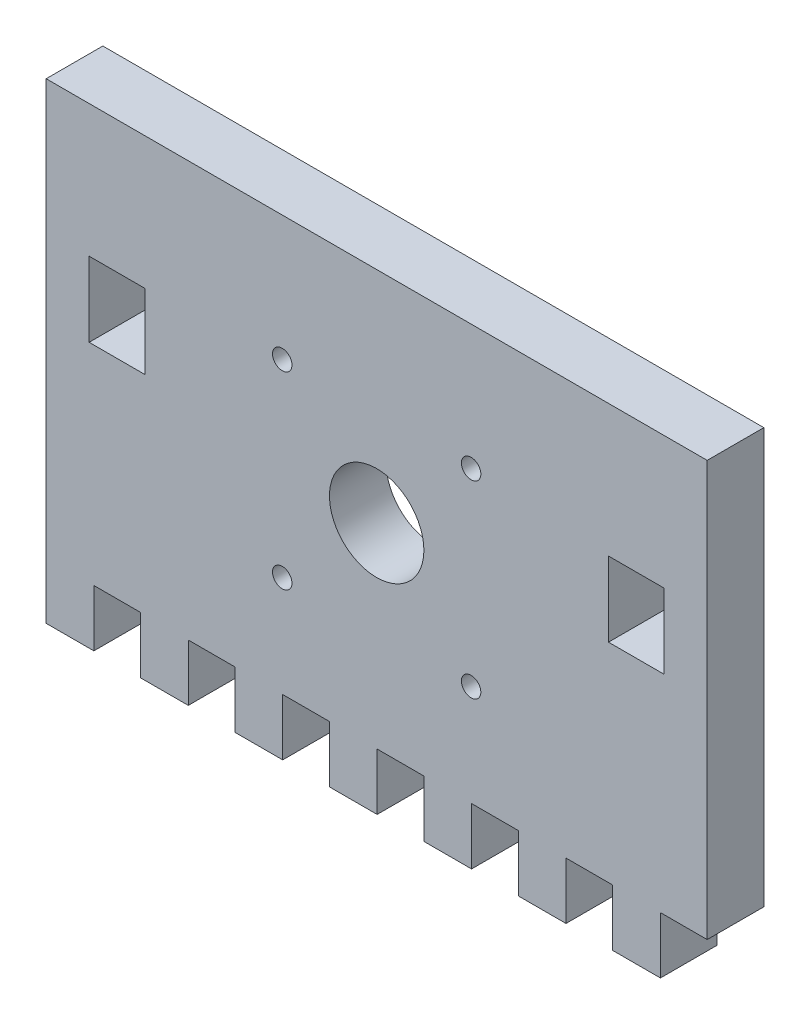
SolidWorks part; units mm, degrees
ref_plane "Plan de face" through (0, 0, 0) normal (0, 0, 1) x (1, 0, 0)
ref_plane "Plan de dessus" through (0, 0, 0) normal (0, 1, 0) x (1, 0, 0)
ref_plane "Plan de droite" through (0, 0, 0) normal (1, 0, 0) x (0, 0, -1)
sketch "Esquisse1" plane through (0, 0, 0) normal (0, 0, 1) x (1, 0, 0)
  line L0 (0, 0) -> (0, 49.95)
  line L1 (0, 49.95) -> (70, 49.95)
  line L2 (70, 49.95) -> (70, 6)
  line L3 (70, 6) -> (65.05, 6)
  line L4 (65.05, 6) -> (65.05, 0)
  line L5 (65.05, 0) -> (60, 0)
  line L6 (60, 0) -> (60, 6)
  line L7 (60, 6) -> (55.05, 6)
  line L8 (55.05, 6) -> (55.05, 0)
  line L10 (30, 0) -> (30, 6)
  line L11 (30, 6) -> (25.05, 6)
  line L12 (25.05, 6) -> (25.05, 0)
  line L13 (25.05, 0) -> (20, 0)
  line L14 (20, 0) -> (20, 6)
  line L15 (20, 6) -> (15.05, 6)
  line L16 (15.05, 6) -> (15.05, 0)
  line L17 (15.05, 0) -> (10, 0)
  line L18 (10, 0) -> (10, 6)
  line L19 (10, 6) -> (5.05, 6)
  line L20 (5.05, 6) -> (5.05, 0)
  line L21 (5.05, 0) -> (0, 0)
  line L22 (30, 0) -> (35.05, 0)
  line L23 (35.05, 0) -> (35.05, 6)
  line L24 (35.05, 6) -> (40, 6)
  line L25 (40, 6) -> (40, 0)
  line L26 (40, 0) -> (45.05, 0)
  line L27 (45.05, 0) -> (45.05, 6)
  line L28 (45.05, 6) -> (50, 6)
  line L29 (50, 6) -> (50, 0)
  line L30 (50, 0) -> (55.05, 0)
  line L31 (4.55, 32) -> (65.45, 32) construction
  line L32 (4.55, 35.95) -> (10.45, 35.95)
  line L33 (4.55, 35.95) -> (4.55, 28.05)
  line L34 (4.55, 28.05) -> (10.45, 28.05)
  line L35 (10.45, 35.95) -> (10.45, 28.05)
  line L36 (59.55, 35.95) -> (65.45, 35.95)
  line L37 (59.55, 35.95) -> (59.55, 28.05)
  line L38 (59.55, 28.05) -> (65.45, 28.05)
  line L39 (65.45, 35.95) -> (65.45, 28.05)
  line L40 (25, 36.7) -> (25, 16.7) construction
  line L41 (25, 16.7) -> (45, 16.7) construction
  line L42 (45, 16.7) -> (45, 36.7) construction
  line L43 (45, 36.7) -> (25, 36.7) construction
  line L44 (35, 36.7) -> (35, 16.7) construction
  line L45 (25, 26.7) -> (45, 26.7) construction
  line L46 (7.5, 35.95) -> (7.5, 28.05) construction
  line L47 (62.5, 35.95) -> (62.5, 28.05) construction
  line L48 (2.525, 0) -> (2.525, 8.5568) construction
  circle A0 centre (25, 36.7) radius 1.03
  circle A1 centre (45, 36.7) radius 1.03
  circle A2 centre (25, 16.7) radius 1.03
  circle A3 centre (45, 16.7) radius 1.03
  circle A4 centre (35, 26.7) radius 5
  point P54 (35, 26.7)
  dimension "D15" = 2.06
  dimension "D16" = 20.7
  dimension "D17" = 10
  dimension "D1" = 70
  dimension "D2" = 5.05
  dimension "D3" = 4.95
  dimension "D4" = 6
  dimension "D5" = 14
  dimension "D6" = 5.9
  dimension "D7" = 5.9
  dimension "D8" = 7.5
  dimension "D9" = 7.5
  dimension "D10" = 7.9
  dimension "D11" = 7.9
  dimension "D12" = 32
  dimension "D13" = 20
  dimension "D14" = 20
extrude "Boss.-Extru.1" add sketch "Esquisse1" along normal blind 6
